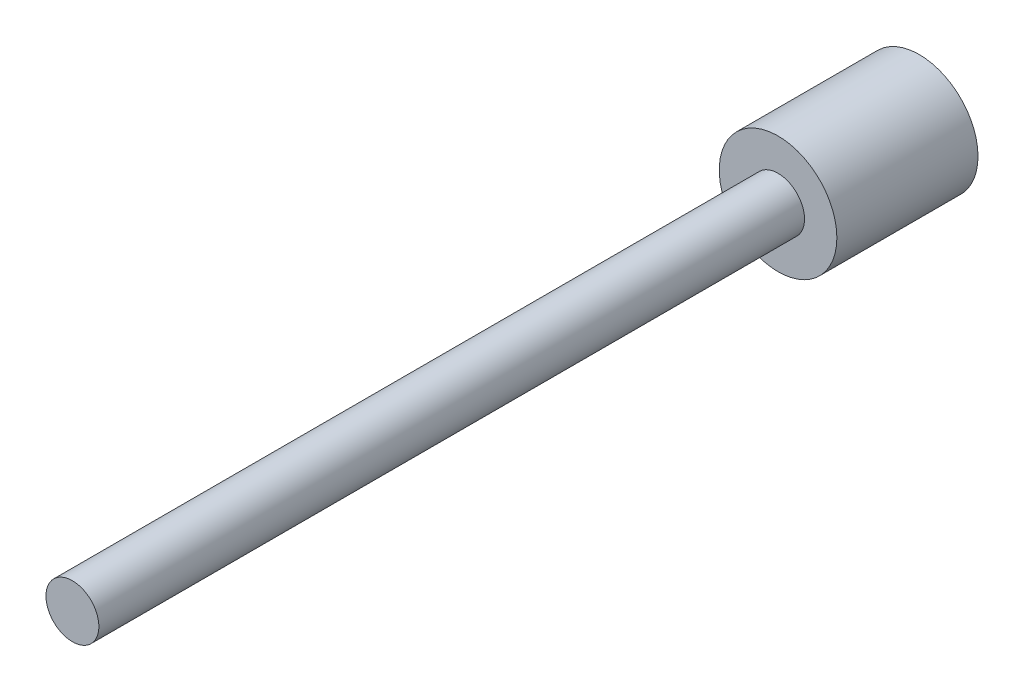
SolidWorks part; units mm, degrees
ref_plane "Front Plane" through (0, 0, 0) normal (0, 0, 1) x (1, 0, 0)
ref_plane "Top Plane" through (0, 0, 0) normal (0, 1, 0) x (1, 0, 0)
ref_plane "Right Plane" through (0, 0, 0) normal (1, 0, 0) x (0, 0, -1)
sketch "Sketch1" plane through (0, 0, 0) normal (0, 0, 1) x (1, 0, 0)
  circle A0 centre (0, 0) radius 5
  circle A1 centre (0, 0) radius 1.5
  dimension "D1" = 10
  dimension "D2" = 3
extrude "Boss-Extrude1" add sketch "Sketch1" along normal blind 10
sketch "Sketch2" plane through (0, 0, 10) normal (0, 0, 1) x (1, 0, 0)
  circle A0 centre (0, 0) radius 5
extrude "Boss-Extrude2" add sketch "Sketch2" along normal blind 2
sketch "Sketch3" plane through (0, 0, 12) normal (0, 0, 1) x (1, 0, 0)
  circle A0 centre (0, 0) radius 2.25
  dimension "D1" = 4.5
extrude "Boss-Extrude3" add sketch "Sketch3" along normal blind 60
